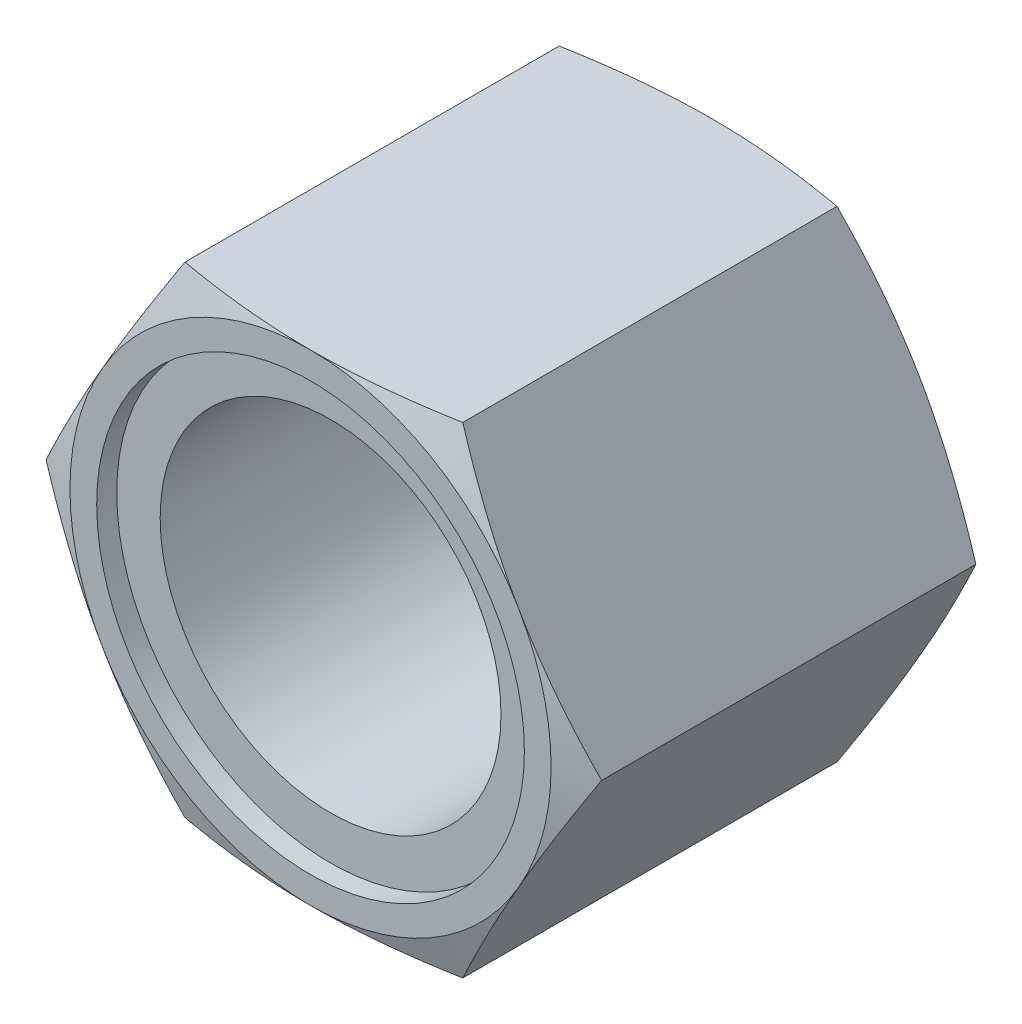
SolidWorks part; units mm, degrees
ref_plane "Плоскость1" through (0, 0, 0) normal (0, 0, 1) x (1, 0, 0)
ref_plane "Плоскость2" through (0, 0, 0) normal (0, 1, 0) x (1, 0, 0)
ref_plane "Плоскость3" through (0, 0, 0) normal (1, 0, 0) x (0, 0, -1)
sketch "Эскиз1" plane through (0, 0, 0) normal (0, 0, 1) x (1, 0, 0)
  line L1 (10.3923, 18) -> (-10.3923, 18)
  line L2 (-10.3923, 18) -> (-20.7846, 0)
  line L3 (-20.7846, 0) -> (-10.3923, -18)
  line L4 (-10.3923, -18) -> (10.3923, -18)
  line L5 (10.3923, -18) -> (20.7846, 0)
  line L6 (20.7846, 0) -> (10.3923, 18)
  circle A0 centre (0, 0) radius 18 construction
  dimension "D1" = 36
extrude "Вытянуть1" add sketch "Эскиз1" along normal blind 30
sketch "Эскиз2" plane through (0, 0, 30) normal (0, 0, 1) x (1, 0, 0)
  circle A0 centre (0, 0) radius 12.75
  dimension "D1" = 25.5
extrude "Вырез-Вытянуть1" cut sketch "Эскиз2" against normal blind 25
cosmetic thread "Условное изображение резьбы1" parameters "D2"=27
sketch "Эскиз3" plane through (0, 0, 5) normal (0, 0, 1) x (1, 0, 0)
  circle A0 centre (0, 0) radius 13.5
  dimension "D1" = 27
extrude "Вырез-Вытянуть2" cut sketch "Эскиз3" along normal blind 4
sketch "Эскиз4" plane through (0, 0, 30) normal (0, 0, 1) x (1, 0, 0)
  circle A0 centre (0, 0) radius 16
  dimension "D1" = 32
extrude "Вырез-Вытянуть3" cut sketch "Эскиз4" against normal blind 1.5
sketch "Эскиз5" plane through (0, 0, 0) normal (0, 1, 0) x (1, 0, 0)
  line L0 (20.7846, -30) -> (20.7846, -29)
  line L1 (20.7846, -30) -> (20.7846, 0) construction
  line L2 (20.7846, -29) -> (18, -30)
  line L3 (20.7846, -30) -> (10.3923, -30) construction
  line L4 (18, -30) -> (20.7846, -30)
  line L5 (20.7846, 0) -> (18, 0)
  line L6 (20.7846, 0) -> (10.3923, 0) construction
  line L7 (18, 0) -> (20.7846, -1)
  line L8 (20.7846, -1) -> (20.7846, 0)
  dimension "D1" = 1
  dimension "D2" = 2
ref_axis "Ось1" through (0, 0, 28.5) along (0, 0, -1)
revolve "Вырез-Повернуть1" cut sketch "Эскиз5" angle 360 about axis through (0, 0, 28.5) along (0, 0, -1)
